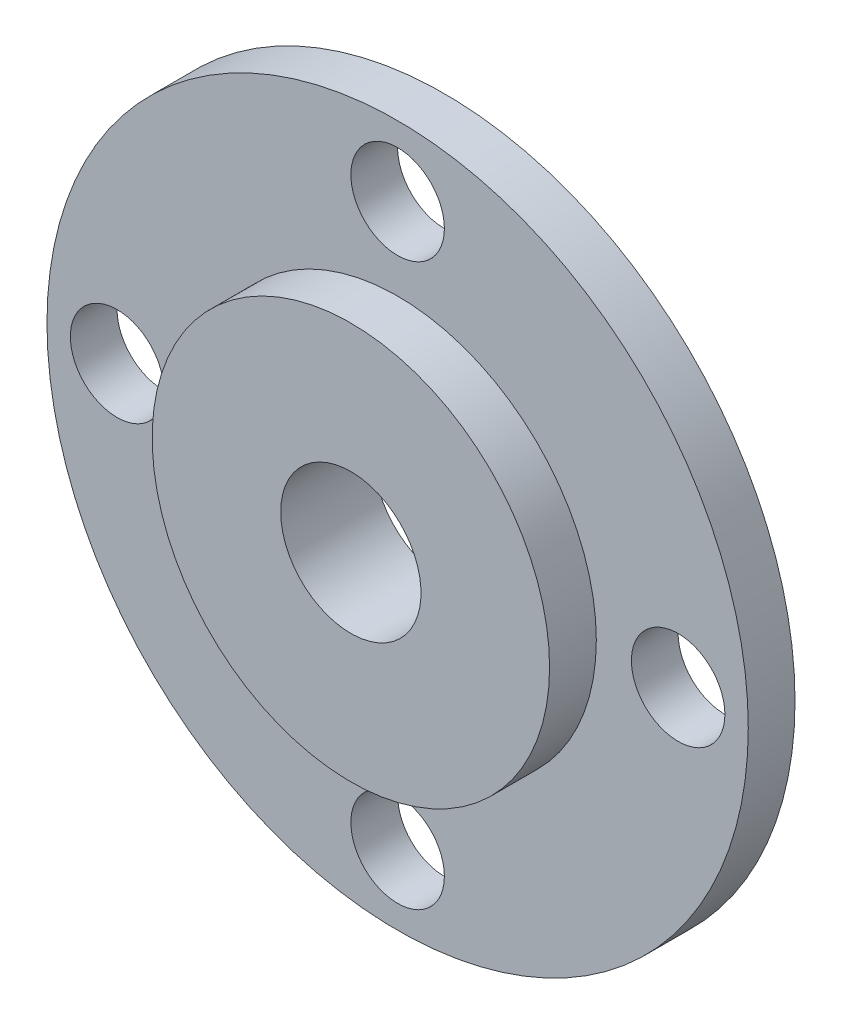
SolidWorks part; units mm, degrees
ref_plane "前视基准面" through (0, 0, 0) normal (0, 0, 1) x (1, 0, 0)
ref_plane "上视基准面" through (0, 0, 0) normal (0, 1, 0) x (1, 0, 0)
ref_plane "右视基准面" through (0, 0, 0) normal (1, 0, 0) x (0, 0, -1)
sketch "草图1" plane through (0, 0, 0) normal (0, 0, 1) x (1, 0, 0)
  circle A0 centre (0, 0) radius 4.25
  dimension "D1" = 8.5
extrude "凸台-拉伸1" add sketch "草图1" along normal blind 1
sketch "草图2" plane through (0, 0, 0) normal (0, 0, -1) x (-1, 0, 0)
  circle A0 centre (0, 0) radius 7.5
  dimension "D1" = 15
extrude "凸台-拉伸2" add sketch "草图2" along normal blind 1
sketch "草图3" plane through (0, 0, 0) normal (0, 0, 1) x (1, 0, 0)
  line L0 (-18.6056, 0) -> (20.7729, 0) construction
  line L1 (0, 17.317) -> (0, -16.6818) construction
  circle A0 centre (6, 0) radius 1
  circle A1 centre (0, 6) radius 1
  circle A2 centre (-6, 0) radius 1
  circle A3 centre (0, -6) radius 1
  dimension "D1" = 2
  dimension "D2" = 6
  dimension "D3" = 6
  dimension "D4" = 6
  dimension "D5" = 6
extrude "切除-拉伸1" cut sketch "草图3" against normal blind 1
sketch "草图4" plane through (0, 0, -1) normal (0, 0, -1) x (-1, 0, 0)
  circle A0 centre (0, 0) radius 1.5
  dimension "D1" = 3
extrude "切除-拉伸2" cut sketch "草图4" against normal through all
